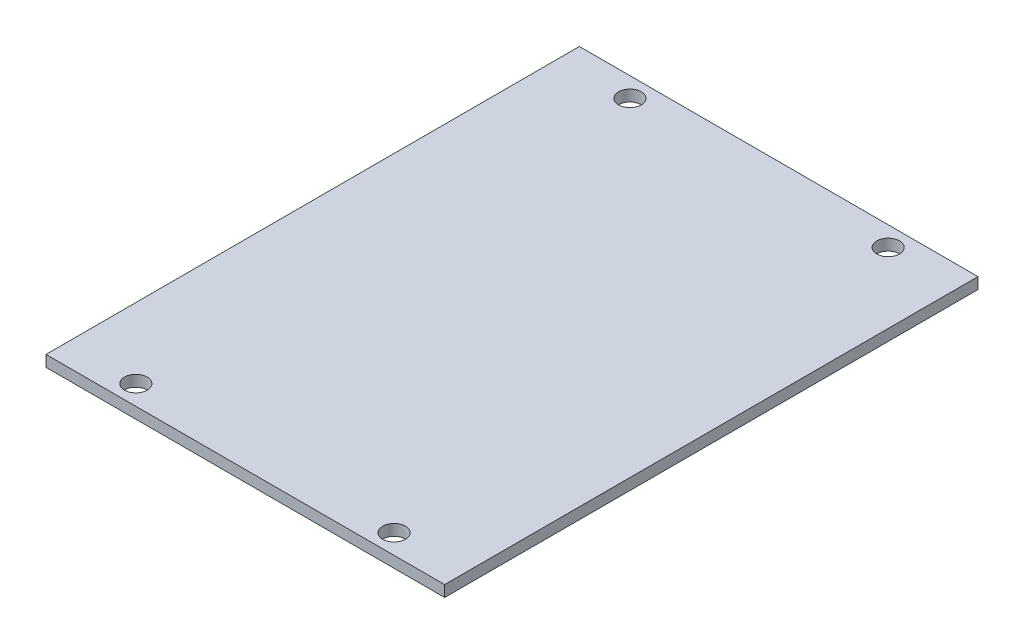
SolidWorks part; units mm, degrees
material "PLA"
ref_plane "Front Plane" through (0, 0, 0) normal (0, 0, 1) x (1, 0, 0)
ref_plane "Top Plane" through (0, 0, 0) normal (0, 1, 0) x (1, 0, 0)
ref_plane "Right Plane" through (0, 0, 0) normal (1, 0, 0) x (0, 0, -1)
sketch "Sketch1" plane through (0, 0, 0) normal (0, 1, 0) x (1, 0, 0)
  line L1 (-35.5, -47.5) -> (35.5, -47.5)
  line L2 (-35.5, -47.5) -> (-35.5, 47.5)
  line L3 (-35.5, 47.5) -> (35.5, 47.5)
  line L4 (35.5, -47.5) -> (35.5, 47.5)
  line L5 (-35.5, -47.5) -> (35.5, 47.5) construction
  line L6 (-35.5, 47.5) -> (35.5, -47.5) construction
  point P0 (0, 0)
  dimension "D1" = 95
  dimension "48" = 71
extrude "Boss-Extrude1" add sketch "Sketch1" along normal blind 2
sketch "Sketch2" plane through (0, 2, 0) normal (0, 1, 0) x (1, 0, 0)
  line L2 (0, -55) -> (0, 55) construction
  line L3 (-55, 0) -> (55, 0) construction
  circle A0 centre (-23, 44) radius 2.025
  circle A1 centre (23, 44) radius 2.025
  circle A2 centre (-23, -44) radius 2.025
  circle A3 centre (23, -44) radius 2.025
  dimension "D1" = 4.05
  dimension "D2" = 46
  dimension "D3" = 88
  dimension "D4" = 4.05
  dimension "D5" = 4.05
  dimension "D6" = 4.05
extrude "Cut-Extrude1" cut sketch "Sketch2" against normal through all
